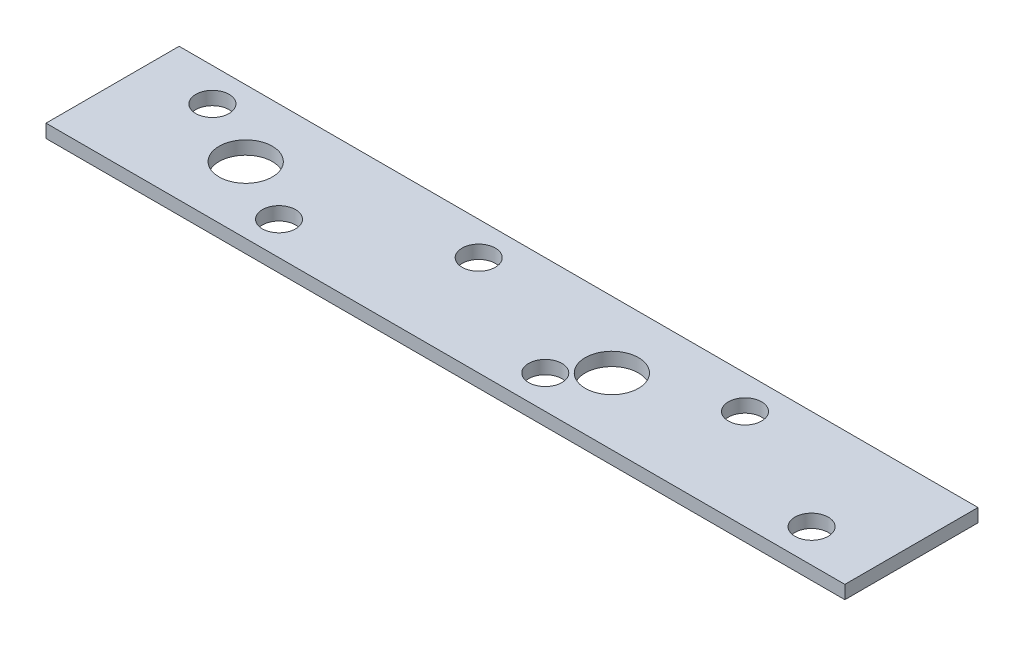
SolidWorks part; units mm, degrees
ref_plane "Спереди" through (0, 0, 0) normal (0, 0, 1) x (1, 0, 0)
ref_plane "Сверху" through (0, 0, 0) normal (0, 1, 0) x (1, 0, 0)
ref_plane "Справа" through (0, 0, 0) normal (1, 0, 0) x (0, 0, -1)
sketch "Эскиз2" plane through (0, 0, 0) normal (0, 1, 0) x (1, 0, 0)
  line L0 (-50, 5) -> (-30, -5) construction
  line L1 (-60, 10) -> (60, 10)
  line L2 (-60, 10) -> (-60, -10)
  line L3 (-60, -10) -> (60, -10)
  line L4 (60, 10) -> (60, -10)
  line L5 (-60, 10) -> (60, -10) construction
  line L6 (-60, -10) -> (60, 10) construction
  circle A0 centre (-50, 5) radius 2.5
  circle A1 centre (-30, 5) radius 2.5 construction
  circle A2 centre (-10, 5) radius 2.5
  circle A3 centre (10, 5) radius 2.5 construction
  circle A4 centre (30, 5) radius 2.5
  circle A5 centre (50, 5) radius 2.5 construction
  circle A6 centre (-30, -5) radius 2.5
  circle A7 centre (-10, -5) radius 2.5 construction
  circle A8 centre (10, -5) radius 2.5
  circle A9 centre (30, -5) radius 2.5 construction
  circle A10 centre (50, -5) radius 2.5
  circle A11 centre (-50, -5) radius 2.5 construction
  circle A12 centre (-40, 0) radius 4
  circle A13 centre (15, 0) radius 4
  point P0 (0, 0)
  point P34 (0, 0)
  dimension "D3" = 5
  dimension "D10" = 8
  dimension "D11" = 8
  dimension "D1" = 20
  dimension "D2" = 120
  dimension "D4" = 5
  dimension "D5" = 10
  dimension "D9" = 5
  dimension "D8" = 40
  dimension "D12" = 55
  dimension "D6" = 6
  dimension "D7" = 2
extrude "Бобышка-Вытянуть1" add sketch "Эскиз2" along normal blind 2
equation "\"print_offset\"= 0.5"
equation "\"tape_width\"=51"
equation "\"tape_thikness\"=5"
equation "\"tape_distance\"=5"
equation "\"screw_d\"=3"
equation "\"screw_hh_d\"=5.3"
equation "\"nut_d\"=5.5"
equation "\"nut_h\"=2.5"
equation "\"sitting_screws\"=30"
equation "\"mount_size\"=42"
equation "\"hip_to_tube\" = 65"
equation "\"back_to_tube\"= 60"
equation "\"tube_d\"= 16"
equation "\"bearing_d1\"= 20"
equation "\"bearing_d2\"= 42"
equation "\"bearing_h\"= 12"
equation "\"tube_A\"= 250"
equation "\"tube_B\"= 384"
equation "\"tube_C\"= 300"
equation "\"tube_thikness\"=1"
equation "\"tube_bend_radius\"= 80"
equation "\"plate_a\"= 20"
equation "\"plate_b\"= 120"
equation "\"plate_holes\"= 5"
equation "\"plate_holes_a\"= ( 2.5 + 7.5 ) / 2"
equation "\"plate_holes_b\"= ( 7.5 + 12.5 ) / 2"
equation "\"plate_holes_step\"= 40"
equation "\"D1@Эскиз2\"=\"plate_a\""
equation "\"D2@Эскиз2\"=\"plate_b\""
equation "\"D3@Эскиз2\"=\"plate_holes\""
equation "\"D4@Эскиз2\"=\"plate_holes\""
equation "\"D9@Эскиз2\"=\"D4@Эскиз2\""
equation "\"D5@Эскиз2\"=\"plate_holes_b\""
equation "\"D8@Эскиз2\"=\"plate_holes_step\""
